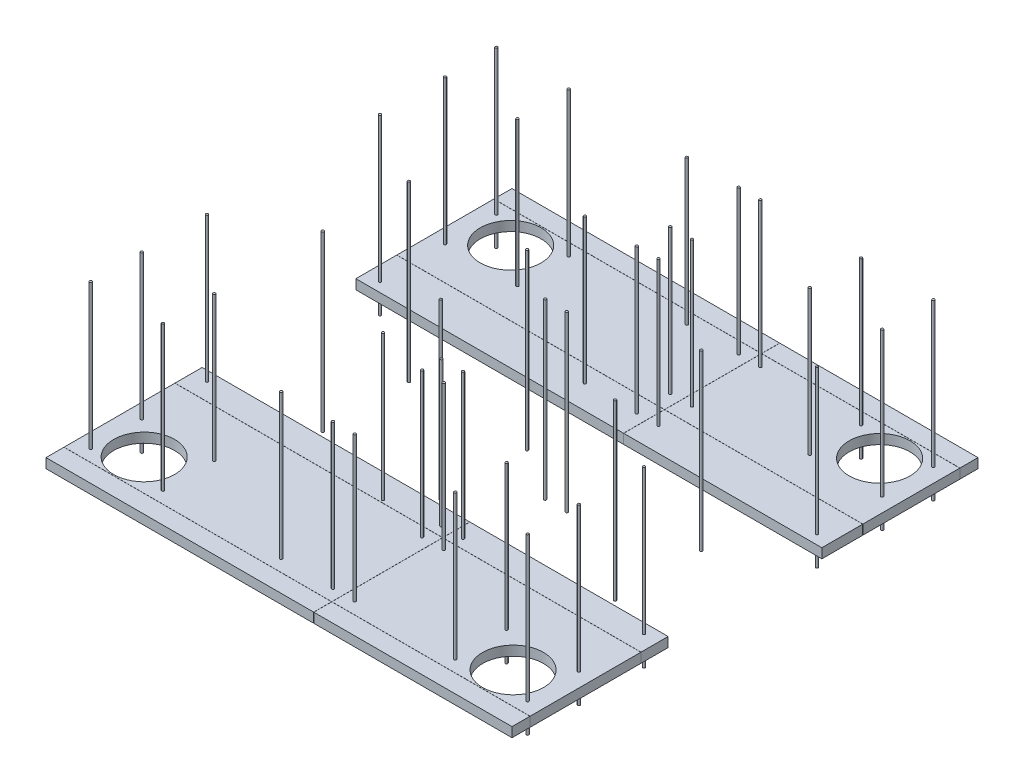
SolidWorks part; units mm, degrees
ref_plane "Front" through (0, 0, 0) normal (0, 0, 1) x (1, 0, 0)
ref_plane "Top" through (0, 0, 0) normal (0, 1, 0) x (1, 0, 0)
ref_plane "Right" through (0, 0, 0) normal (1, 0, 0) x (0, 0, -1)
sketch "Sketch1" plane through (0, 0, 0) normal (0, 1, 0) x (1, 0, 0)
  line L1 (-2454.275, 2454.275) -> (2454.275, 2454.275)
  line L2 (-2454.275, 2454.275) -> (-2454.275, -2454.275)
  line L3 (-2454.275, -2454.275) -> (2454.275, -2454.275)
  line L4 (2454.275, 2454.275) -> (2454.275, -2454.275)
  line L5 (-2454.275, 2454.275) -> (2454.275, -2454.275) construction
  line L6 (-2454.275, -2454.275) -> (2454.275, 2454.275) construction
  point P0 (0, 0)
  dimension "D1" = 4908.55
  dimension "D2" = 4908.55
extrude "Boss-Extrude1" add sketch "Sketch1" along normal blind 101.6
sketch "Sketch2" plane through (0, 101.6, 0) normal (0, 1, 0) x (1, 0, 0)
  line L0 (-2454.275, 2454.275) -> (-2454.275, -2454.275) construction
  line L1 (2454.275, -809.625) -> (-2454.275, -809.625)
  line L2 (2454.275, -809.625) -> (2454.275, 809.625)
  line L3 (2454.275, 809.625) -> (-2454.275, 809.625)
  line L4 (-2454.275, -809.625) -> (-2454.275, 809.625)
  line L5 (2454.275, -809.625) -> (-2454.275, 809.625) construction
  line L6 (2454.275, 809.625) -> (-2454.275, -809.625) construction
  point P0 (0, 0)
  dimension "D1" = 1619.25
extrude "Cut-Extrude1" cut sketch "Sketch2" against normal through all
sketch "Sketch4" plane through (0, 101.6, 0) normal (0, 1, 0) x (1, 0, 0)
  line L0 (-2454.275, -2263.775) -> (2454.275, -2263.775)
  line L3 (-2454.275, -2454.275) -> (2454.275, -2454.275) construction
  line L4 (-2454.275, -1095.375) -> (2454.275, -1095.375)
  line L5 (-2454.275, -809.625) -> (-2454.275, -2454.275) construction
  line L6 (-2454.275, -809.625) -> (2454.275, -809.625) construction
  line L7 (-2454.275, 2263.775) -> (2454.275, 2263.775)
  line L10 (-2454.275, 1241.425) -> (2454.275, 1241.425)
  line L11 (-2454.275, 2454.275) -> (-2454.275, 809.625) construction
  line L12 (2454.275, 809.625) -> (2454.275, 2454.275) construction
  line L13 (2454.275, 2454.275) -> (-2454.275, 2454.275) construction
  line L14 (2454.275, 809.625) -> (-2454.275, 809.625) construction
  line L15 (-2454.275, -1095.375) -> (-2454.275, -2263.775) construction
  line L16 (2454.275, -1095.375) -> (2454.275, -2263.775) construction
  line L17 (2454.275, 1241.425) -> (2454.275, 2263.775) construction
  line L18 (-2454.275, 1241.425) -> (-2454.275, 2263.775) construction
  line L19 (2454.275, -2454.275) -> (2454.275, -809.625) construction
  dimension "D1" = 190.5
  dimension "D2" = 1168.4
  dimension "D3" = 285.75
  dimension "D4" = 190.5
  dimension "D5" = 1022.35
  dimension "D6" = 431.8
extrude "Cut-Extrude-Thin1" cut sketch "Sketch4" against normal through all thin
sketch "Sketch5" plane through (0, 101.6, 0) normal (0, 1, 0) x (1, 0, 0)
  line L0 (365.125, -2454.275) -> (365.125, 2454.275)
  line L1 (-2454.275, -2454.275) -> (2454.275, -2454.275) construction
  line L2 (2454.275, 2454.275) -> (-2454.275, 2454.275) construction
  line L3 (2454.275, -2263.775) -> (2454.275, -1096.645) construction
  line L4 (-2454.275, -1096.645) -> (-2454.275, -2263.775) construction
  dimension "D1" = 2089.15
  dimension "D2" = 2819.4
extrude "Cut-Extrude-Thin2" cut sketch "Sketch5" against normal through all and the other way through all thin
sketch "Sketch8" plane through (0, 101.6, 0) normal (0, 1, 0) x (1, 0, 0)
  line L0 (-974.0807, 502.3386) -> (-974.0807, 1597.0052) construction
sketch "Sketch6" plane through (0, 101.6, 0) normal (0, 1, 0) x (1, 0, 0)
  line L0 (1943.1, 1929.13) -> (1943.1, 2262.505) construction
  line L1 (-1943.1, 1929.13) -> (1943.1, 1929.13) construction
  line L2 (-1943.1, 1929.13) -> (-1943.1, -1931.67) construction
  line L3 (-1943.1, -1931.67) -> (1943.1, -1931.67) construction
  line L4 (1943.1, 1929.13) -> (1943.1, -1931.67) construction
  line L5 (-1943.1, -1931.67) -> (-1943.1, -2265.045) construction
  line L6 (-2454.275, -2265.045) -> (365.125, -2265.045) construction
  line L7 (366.395, 2262.505) -> (2454.275, 2262.505) construction
  line L9 (2454.275, 1241.425) -> (2454.275, 2262.505) construction
  line L11 (-2454.275, -1096.645) -> (-2454.275, -2263.775) construction
  circle A0 centre (1943.1, 1929.13) radius 320.675
  circle A1 centre (-1943.1, 1929.13) radius 320.675
  circle A2 centre (-1943.1, -1931.67) radius 320.675
  circle A3 centre (1943.1, -1931.67) radius 320.675
  dimension "D1" = 641.35
  dimension "D3" = 190.5
  dimension "D4" = 190.5
  dimension "D2" = 12.7
extrude "DUCT HOLES" cut sketch "Sketch6" against normal through all
sketch "Sketch7" plane through (0, 101.6, 0) normal (0, 1, 0) x (1, 0, 0)
  line L0 (-1539.875, 2301.875) -> (-295.275, 2301.875) construction
  line L1 (-1539.875, 2301.875) -> (-2454.275, 2301.875) construction
  line L2 (-2454.275, 2454.275) -> (-2454.275, 2263.775) construction
  line L3 (365.125, 2454.275) -> (-2454.275, 2454.275) construction
  line L4 (-295.275, 2301.875) -> (365.125, 2301.875) construction
  line L5 (365.125, 2263.775) -> (365.125, 2454.275) construction
  line L6 (1539.875, 1597.025) -> (1539.875, 1063.625) construction
  line L7 (365.125, 2301.875) -> (974.725, 2301.875) construction
  line L8 (974.725, 2301.875) -> (1539.875, 2301.875) construction
  line L9 (1539.875, 2301.875) -> (2454.275, 2301.875) construction
  line L10 (2454.275, 2263.775) -> (2454.275, 2454.275) construction
  line L11 (366.395, 2263.775) -> (366.395, 2454.275) construction
  line L12 (2454.275, 1597.025) -> (-2454.275, 1597.025) construction
  line L13 (2454.275, 1241.425) -> (2454.275, 2262.505) construction
  line L14 (-2454.275, 2262.505) -> (-2454.275, 1241.425) construction
  line L15 (1539.875, 2301.875) -> (1539.875, 1597.025) construction
  line L16 (-2454.275, 1241.425) -> (365.125, 1241.425) construction
  line L17 (-295.275, 2301.875) -> (-295.275, 1597.025) construction
  line L18 (974.725, 2301.875) -> (974.725, 1597.025) construction
  line L19 (-2454.275, 2136.775) -> (2454.275, 2136.775) construction
  line L20 (-2454.275, 2263.775) -> (365.125, 2263.775) construction
  line L21 (-1539.875, 2301.875) -> (-1539.875, 2136.775) construction
  line L22 (-2454.275, 1063.625) -> (2454.275, 1063.625) construction
  line L23 (-2454.275, 1240.155) -> (-2454.275, 809.625) construction
  line L24 (2454.275, 809.625) -> (2454.275, 1240.155) construction
  line L25 (365.125, 809.625) -> (-2454.275, 809.625) construction
  line L26 (-1539.875, 1063.625) -> (-1539.875, 1597.025) construction
  line L27 (-295.275, 1597.025) -> (-295.275, 1063.625) construction
  line L28 (-2107.4102, -2022.1425) -> (-2107.4102, -819.4758) construction
  line L29 (-1539.875, 1285.875) -> (1539.875, 1285.875) construction
  line L30 (-2301.875, 1597.025) -> (-2301.875, 1063.625) construction
  line L31 (2301.875, 1597.025) -> (2301.875, 1063.625) construction
  line L32 (-2454.275, 1240.155) -> (365.125, 1240.155) construction
  line L33 (479.425, 1063.625) -> (250.825, 1063.625) construction
  line L34 (479.425, 1063.625) -> (479.425, 1416.685) construction
  line L35 (479.425, 1416.685) -> (250.825, 1416.685) construction
  line L36 (250.825, 1063.625) -> (250.825, 1416.685) construction
  line L37 (-2454.275, 1240.155) -> (365.125, 1240.155) construction
  line L38 (365.125, 809.625) -> (365.125, 1240.155) construction
  line L39 (365.125, 809.625) -> (365.125, 1240.155) construction
  line L40 (440.6472, 1241.425) -> (440.6472, 1063.625) construction
  line L41 (250.825, -1198.245) -> (479.425, -1198.245) construction
  line L42 (250.825, -1198.245) -> (250.825, -995.045) construction
  line L43 (250.825, -995.045) -> (479.425, -995.045) construction
  line L44 (479.425, -1198.245) -> (479.425, -995.045) construction
  line L45 (366.395, 1241.425) -> (2454.275, 1241.425) construction
  line L46 (1539.875, 1063.625) -> (1539.875, -2454.275) construction
  line L47 (366.395, -2454.275) -> (2454.275, -2454.275) construction
  line L48 (-2454.275, -1096.645) -> (365.125, -1096.645) construction
  line L49 (-2454.275, -1096.645) -> (365.125, -1096.645) construction
  line L50 (-2301.875, 1063.625) -> (-2301.875, 911.225) construction
  line L51 (-2301.875, 911.225) -> (2301.875, 911.225) construction
  line L52 (2301.875, 911.225) -> (2301.875, 1063.625) construction
  line L53 (-1539.875, 1063.625) -> (-1539.875, -2454.275) construction
  line L54 (-2454.275, -2454.275) -> (365.125, -2454.275) construction
  line L55 (1539.875, 454.025) -> (-1539.875, 454.025) construction
  line L56 (250.825, 1063.625) -> (250.825, -2454.275) construction
  line L57 (479.425, 1063.625) -> (479.425, -2454.275) construction
  line L58 (-295.275, 1063.625) -> (-295.275, -2454.275) construction
  line L59 (479.425, 98.425) -> (250.825, 98.425) construction
  line L60 (479.425, 1063.625) -> (479.425, 2301.875) construction
  line L61 (250.825, 1063.625) -> (250.825, 2301.875) construction
  circle A0 centre (-1539.875, 2301.875) radius 12.7 construction
  circle A4 centre (1539.875, 1597.025) radius 12.7
  circle A5 centre (-1539.875, 1597.025) radius 12.7
  circle A6 centre (479.425, 1063.625) radius 12.7
  circle A7 centre (-295.275, 1597.025) radius 12.7 construction
  circle A8 centre (974.725, 1597.025) radius 12.7 construction
  circle A9 centre (-295.275, 2136.775) radius 12.7
  circle A10 centre (-1539.875, 2136.775) radius 12.7
  circle A11 centre (974.725, 2136.775) radius 12.7 construction
  circle A12 centre (1539.875, 2136.775) radius 12.7
  circle A13 centre (-295.275, 1063.625) radius 12.7
  circle A14 centre (-1539.875, 1063.625) radius 12.7 construction
  circle A15 centre (1539.875, 1063.625) radius 12.7 construction
  circle A16 centre (-2301.875, 1597.025) radius 12.7
  circle A17 centre (2301.875, 1597.025) radius 12.7
  circle A18 centre (-2301.875, 2136.775) radius 12.7
  circle A19 centre (2301.875, 2136.775) radius 12.7
  circle A20 centre (219.075, 2301.875) radius 12.7 construction
  circle A21 centre (658.495, 2301.875) radius 12.7 construction
  circle A22 centre (1539.875, 2301.875) radius 12.7 construction
  circle A23 centre (-650.875, 2301.875) radius 12.7 construction
  circle A24 centre (-1539.875, 1285.875) radius 12.7 construction
  circle A25 centre (1539.875, 1285.875) radius 12.7 construction
  circle A26 centre (-2301.875, 1063.625) radius 12.7 construction
  circle A27 centre (2301.875, 1063.625) radius 12.7 construction
  circle A28 centre (250.825, 1416.685) radius 12.7
  circle A29 centre (479.425, 1416.685) radius 12.7
  circle A30 centre (250.825, 1063.625) radius 12.7
  circle A31 centre (479.425, -995.045) radius 12.7
  circle A32 centre (250.825, -995.045) radius 12.7
  circle A33 centre (250.825, -1198.245) radius 12.7
  circle A34 centre (479.425, -1198.245) radius 12.7
  circle A35 centre (-2301.875, 911.225) radius 12.7
  circle A36 centre (2301.875, 911.225) radius 12.7
  circle A37 centre (1539.875, 454.025) radius 12.7
  circle A38 centre (-1539.875, 454.025) radius 12.7
  circle A41 centre (-295.275, 454.025) radius 12.7
  circle A43 centre (479.425, 98.425) radius 12.7
  circle A44 centre (250.825, 98.425) radius 12.7
  circle A45 centre (250.825, 2136.775) radius 12.7
  circle A47 centre (479.425, 2136.775) radius 12.7
  point P107 (250.825, -1096.645)
  point P138 (0, 0)
  dimension "D1" = 25.4
  dimension "D5" = 609.6
  dimension "D7" = 355.6
  dimension "D11" = 152.4
  dimension "D14" = 152.4
  dimension "D19" = 889
  dimension "D20" = 914.4
  dimension "D21" = 1168.4
  dimension "D25" = 457.2
  dimension "D26" = 355.6
  dimension "D2" = 152.4
  dimension "D3" = 914.4
  dimension "D4" = 660.4
  dimension "D6" = 914.4
  dimension "D8" = 914.4
  dimension "D9" = 127
  dimension "D10" = 152.4
  dimension "D12" = 254
  dimension "D13" = 228.6
  dimension "D15" = 152.4
  dimension "D16" = 146.05
  dimension "D17" = 292.1
  dimension "D18" = 914.4
  dimension "D22" = 3079.75
  dimension "D23" = 203.2
  dimension "D24" = 152.4
extrude "UNISTRUT STUD LAYOUT" add sketch "Sketch7" along normal blind 1524 and the other way blind 304.8 separate body
mirror "Mirror3" about plane through (0, 0, 0) normal (0, 0, 1) of bodies 251 238 222 252 271 272 286 302 301 306 309 305 316 315 317 320 321 240 223 227 214 225 241 215 226 224 228 217 244 229 216 275 276 277 281 283 287 288 293 291
